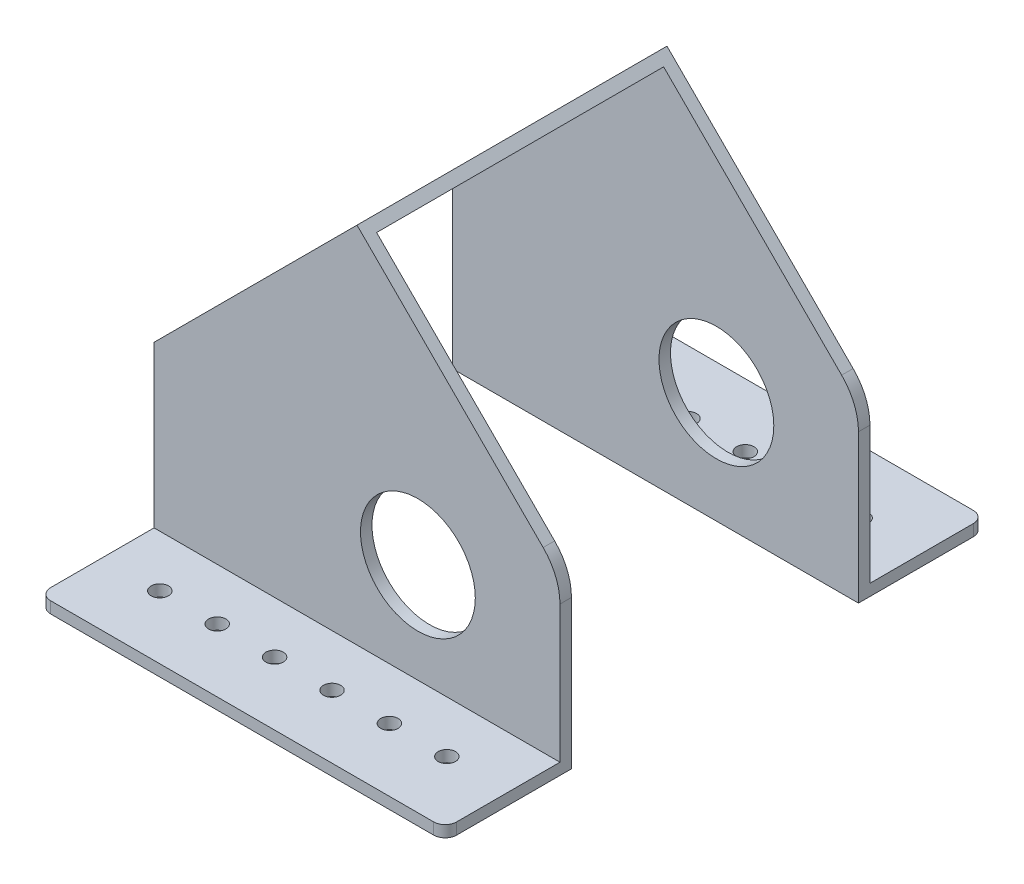
SolidWorks part; units mm, degrees
ref_plane "前视基准面" through (0, 0, 0) normal (0, 0, 1) x (1, 0, 0)
ref_plane "上视基准面" through (0, 0, 0) normal (0, 1, 0) x (1, 0, 0)
ref_plane "右视基准面" through (0, 0, 0) normal (1, 0, 0) x (0, 0, -1)
sketch "草图1" plane through (0, 0, 0) normal (0, 0, 1) x (1, 0, 0)
  line L0 (0, 0) -> (0, 30)
  line L1 (0, 30) -> (35.3553, 65.3553)
  line L4 (35.3553, 65.3553) -> (67.7817, 32.9289)
  line L5 (70.7107, 25.8579) -> (70.7107, 0)
  line L6 (70.7107, 0) -> (0, 0)
  line L7 (17.6777, 47.6777) -> (45.9619, 19.3934) construction
  circle A0 centre (45.9619, 19.3934) radius 10
  arc A1 (67.7817, 32.9289) -> (70.7107, 25.8579) centre (60.7107, 25.8579) cw
  dimension "D1" = 10
extrude "凸台-拉伸1" add sketch "草图1" along normal blind 2
sketch "草图2" plane through (-15, 15, 0) normal (-0.7071, 0.7071, 0) x (0, 0, 1)
  line L0 (0, 71.2132) -> (-50, 71.2132)
  line L1 (-50, 71.2132) -> (-50, 21.2132)
  line L2 (-50, 21.2132) -> (0, 21.2132)
  line L3 (0, 71.2132) -> (0, 21.2132)
  line L4 (-25, 46.2132) -> (-25, 61.7132) construction
  line L5 (-25, 61.7132) -> (-40.5, 61.7132) construction
  circle A0 centre (-25, 46.2132) radius 11.5
  circle A1 centre (-40.5, 61.7132) radius 1.51
  circle A2 centre (-9.5, 61.7132) radius 1.51
  circle A3 centre (-9.5, 30.7132) radius 1.51
  circle A4 centre (-40.5, 30.7132) radius 1.51
  dimension "D1" = 2
  dimension "D2" = 2
extrude "凸台-拉伸2" add sketch "草图2" against normal blind 2
sketch "草图3" plane through (0, 0, 0) normal (0, -1, 0) x (1, 0, 0)
  line L0 (0, 2) -> (0, 20)
  line L1 (2, 22) -> (68.7107, 22)
  line L2 (70.7107, 20) -> (70.7107, 2)
  line L3 (0, 2) -> (70.7107, 2) construction
  line L4 (70.7107, 2) -> (0, 2)
  line L5 (0, 11) -> (10, 11) construction
  circle A0 centre (10, 11) radius 1.51
  circle A1 centre (20, 11) radius 1.51
  circle A2 centre (30, 11) radius 1.51
  circle A3 centre (40, 11) radius 1.51
  circle A4 centre (50, 11) radius 1.51
  circle A5 centre (60, 11) radius 1.51
  arc A6 (68.7107, 22) -> (70.7107, 20) centre (68.7107, 20) cw
  arc A7 (0, 20) -> (2, 22) centre (2, 20) cw
  dimension "D1" = 6
  dimension "D2" = 2
extrude "凸台-拉伸3" add sketch "草图3" against normal blind 2
ref_plane "基准面1" through (0, 0, -25) normal (0, 0, -1) x (-1, 0, 0)
mirror "镜向1" about plane through (0, 0, -25) normal (0, 0, -1) of "凸台-拉伸3", "凸台-拉伸1"
